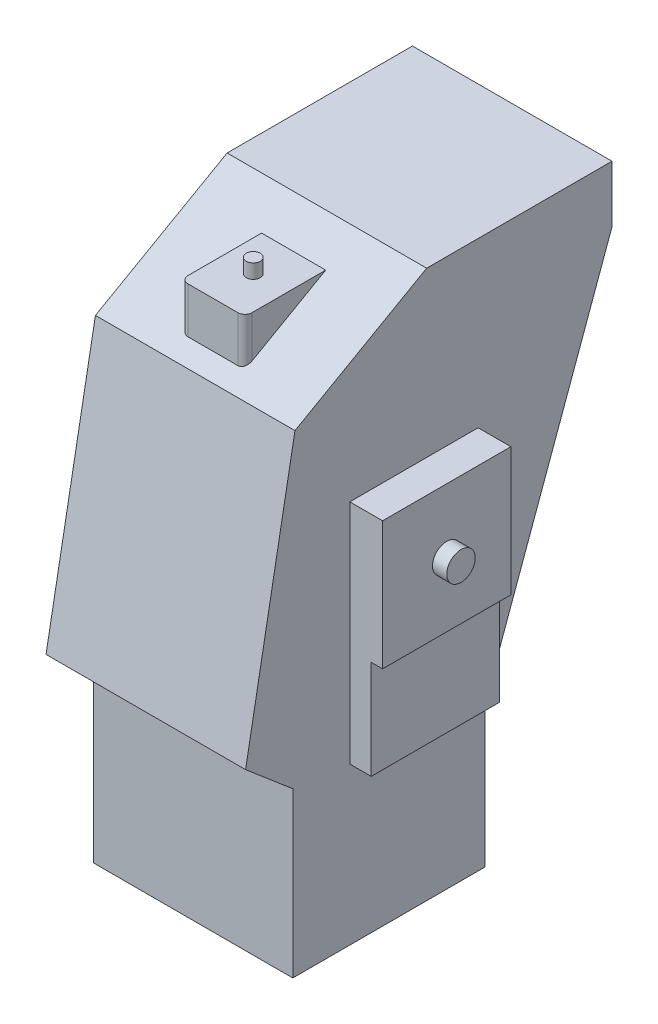
SolidWorks part; units mm, degrees
ref_plane "Front Plane" through (0, 0, 0) normal (0, 0, 1) x (1, 0, 0)
ref_plane "Top Plane" through (0, 0, 0) normal (0, 1, 0) x (1, 0, 0)
ref_plane "Right Plane" through (0, 0, 0) normal (1, 0, 0) x (0, 0, -1)
sketch "Sketch1" plane through (0, 0, 0) normal (1, 0, 0) x (0, 0, -1)
  line L0 (-28.6507, 265) -> (101.3493, 265)
  line L1 (101.3493, 265) -> (101.3493, 225)
  line L2 (101.3493, 225) -> (12.424, -19.3201)
  line L3 (12.424, -19.3201) -> (12.424, -119.3201)
  line L4 (12.424, -119.3201) -> (-122.576, -119.3201)
  line L5 (-122.576, -119.3201) -> (-122.576, -4.3201)
  line L6 (-122.576, -4.3201) -> (-155.7031, 23.8419)
  line L7 (-155.7031, 23.8419) -> (-121.0568, 212.5173)
  line L8 (-121.0568, 212.5173) -> (-28.6507, 265)
  dimension "D1" = 130
  dimension "D2" = 106.27
  dimension "D3" = 160
  dimension "D4" = 130
  dimension "D5" = 191.83
  dimension "D6" = 43.48
  dimension "D7" = 115
  dimension "D8" = 135
  dimension "D9" = 100
  dimension "D10" = 260
  dimension "D11" = 40
extrude "Boss-Extrude1" add sketch "Sketch1" against normal blind 140
ref_plane "Plane1" through (0, 251.75, 0) normal (0, 1, 0) x (1, 0, 0)
sketch "Sketch2" plane through (0, 251.75, 0) normal (0, 1, 0) x (1, 0, 0)
  line L0 (-70, -28.6507) -> (-70, -121.0568) construction
  line L1 (-140, -28.6507) -> (0, -28.6507) construction
  line L2 (-140, -121.0568) -> (0, -121.0568) construction
  line L4 (-47.5, -108.6507) -> (-92.5, -108.6507)
  line L5 (-47.5, -108.6507) -> (-47.5, -48.6507)
  line L6 (-47.5, -48.6507) -> (-92.5, -48.6507)
  line L7 (-92.5, -108.6507) -> (-92.5, -48.6507)
  line L8 (-47.5, -108.6507) -> (-92.5, -48.6507) construction
  line L9 (-47.5, -48.6507) -> (-92.5, -108.6507) construction
  point P6 (-70, -78.6507)
  dimension "D1" = 60
  dimension "D2" = 45
  dimension "D3" = 20
extrude "Boss-Extrude2" add sketch "Sketch2" against normal up to surface (32.1866 mm away)
fillet "Fillet3" radius 5 2 edges at (-47.5, 235.6567, 108.6507) (-92.5, 235.6567, 108.6507)
sketch "Sketch3" plane through (0, 251.75, 0) normal (0, 1, 0) x (1, 0, 0)
  line L0 (-48.9645, -107.1863) -> (-92.5, -51.9799) construction
  arc A0 (-52.5, -108.6507) -> (-47.5, -103.6507) centre (-52.5, -103.6507) ccw construction
  circle A1 centre (-70.7322, -79.5831) radius 4.9
extrude "Boss-Extrude3" add sketch "Sketch3" along normal blind 10
sketch "Sketch5" plane through (0, 0, 0) normal (1, 0, 0) x (0, 0, -1)
  line L0 (101.3493, 265) -> (-28.6507, 265) construction
  line L1 (7.424, 150) -> (-82.576, 150)
  line L2 (7.424, 150) -> (7.424, -9.3201)
  line L3 (7.424, -9.3201) -> (-82.576, -9.3201)
  line L4 (-82.576, 150) -> (-82.576, -9.3201)
  line L5 (-122.576, -119.3201) -> (12.424, -119.3201) construction
  line L6 (12.424, -119.3201) -> (12.424, -19.3201) construction
  dimension "D1" = 115
  dimension "D2" = 110
  dimension "D3" = 90
  dimension "D4" = 5
extrude "Boss-Extrude4" add sketch "Sketch5" along normal blind 15
sketch "Sketch6" plane through (15, 0, 0) normal (1, 0, 0) x (0, 0, -1)
  line L0 (7.424, -9.3201) -> (7.424, 150) construction
  line L1 (-82.576, 150) -> (7.424, 150)
  line L2 (-82.576, 150) -> (-82.576, 60)
  line L3 (-82.576, 60) -> (7.424, 60)
  line L4 (7.424, 150) -> (7.424, 60)
  dimension "D1" = 90
extrude "Boss-Extrude5" add sketch "Sketch6" along normal blind 8
sketch "Sketch7" plane through (23, 0, 0) normal (1, 0, 0) x (0, 0, -1)
  line L0 (-82.576, 150) -> (7.424, 60) construction
  circle A0 centre (-37.576, 105) radius 10
extrude "Boss-Extrude6" add sketch "Sketch7" along normal blind 10
ref_plane "Plane3" through (-70, 0, 0) normal (1, 0, 0) x (0, 0, -1)
mirror "Mirror1" about plane through (-70, 0, 0) normal (1, 0, 0) of "Boss-Extrude4", "Boss-Extrude5", "Boss-Extrude6"
